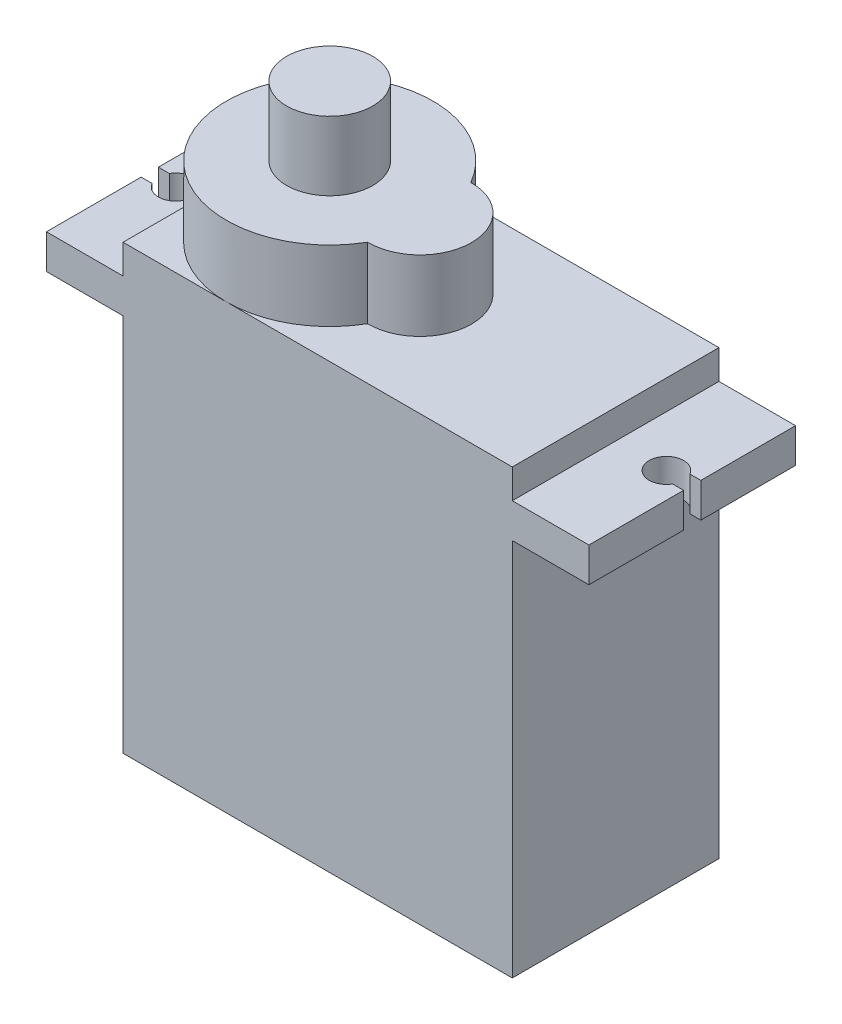
SolidWorks part; units mm, degrees
ref_plane "Piano frontale" through (0, 0, 0) normal (0, 0, 1) x (1, 0, 0)
ref_plane "Piano superiore" through (0, 0, 0) normal (0, 1, 0) x (1, 0, 0)
ref_plane "Piano destro" through (0, 0, 0) normal (1, 0, 0) x (0, 0, -1)
sketch "Schizzo1" plane through (0, 0, 0) normal (0, 1, 0) x (1, 0, 0)
  line L1 (0, 0) -> (22.6, 0)
  line L2 (0, 0) -> (0, 12)
  line L3 (0, 12) -> (22.6, 12)
  line L4 (22.6, 0) -> (22.6, 12)
  dimension "D1" = 22.6
  dimension "D2" = 12
extrude "Estrusione-Estrusione1" add sketch "Schizzo1" along normal blind 22
sketch "Schizzo3" plane through (0, 22, 0) normal (0, 1, 0) x (1, 0, 0)
  line L0 (-4.45, 0) -> (27.05, 0)
  line L1 (27.05, 0) -> (27.05, 12)
  line L2 (27.05, 12) -> (-4.45, 12)
  line L3 (-4.45, 12) -> (-4.45, 0)
  line L4 (0, 12) -> (0, 0) construction
  line L5 (22.6, 0) -> (22.6, 12) construction
  dimension "D1" = 4.45
  dimension "D2" = 4.45
  dimension "D3" = 12
extrude "Estrusione-Estrusione2" add sketch "Schizzo3" along normal blind 2 contours L3 L0 L1 L2
sketch "Schizzo4" plane through (0, 24, 0) normal (0, 1, 0) x (1, 0, 0)
  line L0 (27.05, 12) -> (-4.45, 12) construction
  line L1 (0, 0) -> (22.6, 0)
  line L2 (0, 0) -> (0, 12)
  line L3 (0, 12) -> (22.6, 12)
  line L4 (22.6, 0) -> (22.6, 12)
  line L6 (0, 12) -> (0, 0) construction
  dimension "D1" = 22.6
extrude "Estrusione-Estrusione3" add sketch "Schizzo4" along normal blind 1.7
sketch "Schizzo5" plane through (0, 25.7, 0) normal (0, 1, 0) x (1, 0, 0)
  line L0 (22.6, 12) -> (0, 12) construction
  line L2 (0, 12) -> (0, 0) construction
  line L3 (0, 0) -> (22.6, 0) construction
  circle A0 centre (6, 6) radius 6
  circle A1 centre (11.2364, 6) radius 3
  dimension "D1" = 6
  dimension "D2" = 6
  dimension "D3" = 5.2364
extrude "Estrusione-Estrusione4" add sketch "Schizzo5" along normal blind 4.1 contours A1 A0 | A0 A1 | A0 A1
sketch "Schizzo6" plane through (0, 29.8, 0) normal (0, 1, 0) x (1, 0, 0)
  circle A0 centre (6, 6) radius 2.5
  dimension "D1" = 5
extrude "Estrusione-Estrusione5" add sketch "Schizzo6" along normal blind 4
sketch "Schizzo7" plane through (0, 24, 0) normal (0, 1, 0) x (1, 0, 0)
  line L0 (27.05, 6) -> (-4.45, 6)
  line L1 (27.05, 0) -> (27.05, 12) construction
  line L2 (-4.45, 12) -> (-4.45, 0) construction
  line L4 (-4.45, 5.5) -> (-4.45, 6.5)
  line L5 (27.05, 5.5) -> (27.05, 6.5)
  line L6 (-4.45, 6.5) -> (-2.4491, 6.5)
  line L7 (-2.4491, 6.5) -> (-2.4491, 5.5)
  line L8 (-2.4491, 5.5) -> (-4.45, 5.5)
  line L9 (27.05, 6.5) -> (25.0476, 6.5)
  line L10 (25.0476, 6.5) -> (25.0476, 5.5)
  line L11 (25.0476, 5.5) -> (27.05, 5.5)
  circle A3 centre (-2.95, 6) radius 1
  circle A4 centre (25.55, 6) radius 1
  point P10 (-4.45, 6)
  point P12 (27.05, 6)
  line M3 (27.05, 0) -> (27.05, 12)
  dimension "D1" = 1
  dimension "D2" = 1
  dimension "D3" = 2
  dimension "D4" = 2
  dimension "D5" = 1.5
  dimension "D6" = 1.5
extrude "Taglio-Estrusione2" cut sketch "Schizzo7" against normal up to next contours A3 L0 L4 L8 | A3 L6 L4 L0 | L0 A3 L8 L7 | L0 A3 L6 L7 | L8 A3 L0 L7 | L6 A3 L0 L7 | L11 A4 L0 L10 | L0 A4 L11 L10 | L9 A4 L0 L10 | L0 A4 L9 L10 | A4 L0 L9 M3 | A4 L11 L0 M3
